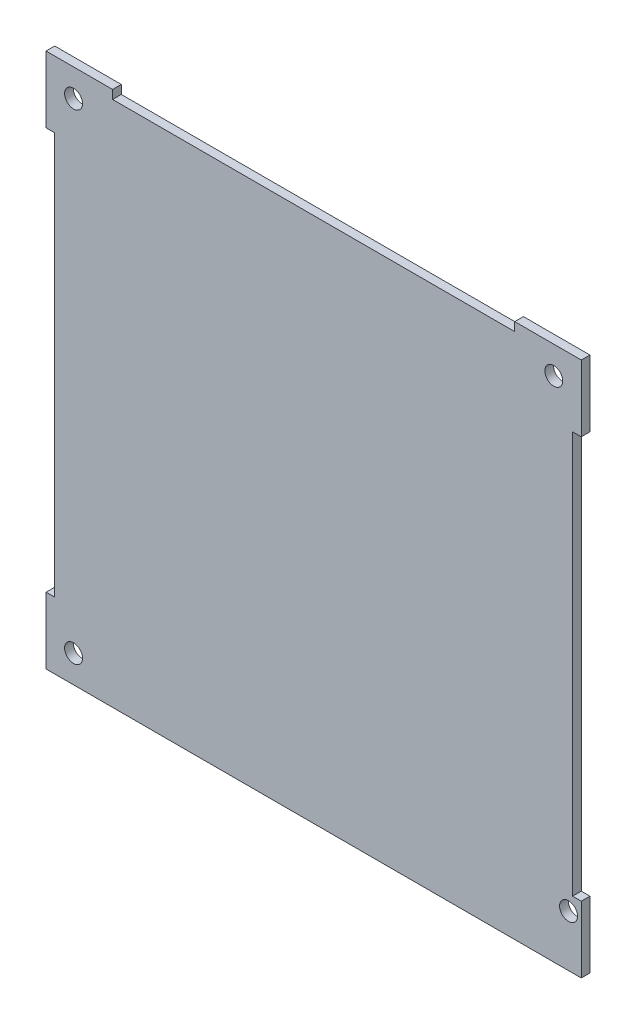
SolidWorks part; units mm, degrees
material "FR4"
ref_plane "Front Plane" through (0, 0, 0) normal (0, 0, 1) x (1, 0, 0)
ref_plane "Top Plane" through (0, 0, 0) normal (0, 1, 0) x (1, 0, 0)
ref_plane "Right Plane" through (0, 0, 0) normal (1, 0, 0) x (0, 0, -1)
sketch "Sketch1" plane through (0, 0, 0) normal (0, 0, 1) x (1, 0, 0)
  line L1 (46.25, -46.25) -> (-46.25, -46.25)
  line L2 (46.25, -46.25) -> (46.25, 46.25)
  line L3 (46.25, 46.25) -> (-46.25, 46.25)
  line L4 (-46.25, -46.25) -> (-46.25, 46.25)
  line L5 (46.25, -46.25) -> (-46.25, 46.25) construction
  line L6 (46.25, 46.25) -> (-46.25, -46.25) construction
  point P0 (0, 0)
  dimension "D1" = 92.5
  dimension "D2" = 92.5
extrude "Boss-Extrude1" add sketch "Sketch1" along normal blind 1.5
hole_wizard "Ø3.1 (3.1) Diameter Hole1" positions "Sketch3" profile "Sketch2" hole size "Ø3.1" standard "ANSI Metric" end condition through all
sketch "Sketch3" plane through (0, 0, 1.5) normal (0, 0, 1) x (1, 0, 0)
  line L0 (46.25, -46.25) -> (46.25, 46.25) construction
  line L1 (-46.25, -46.25) -> (46.25, -46.25) construction
  point P0 (-41.5, 41.5)
  point P2 (41.5, 41.5)
  point P4 (44.05, -37.33)
  point P6 (-41.5, -41.5)
  dimension "D1" = 2.2
  dimension "D2" = 8.92
sketch "Sketch2" plane through (-41.5, 41.5, 1.5) normal (1, 0, 0) x (0, -1, 0)
  line L0 (0, 0) -> (0, 1.5)
  line L1 (0, 1.5) -> (1.55, 1.5)
  line L2 (1.55, 1.5) -> (1.55, 0)
  line L5 (1.55, 0) -> (0, 0)
  line L11 (0, -6.35) -> (0, 107.95) construction
  dimension "Thru Hole Dia." = 3.1
  dimension "Thru Hole Depth" = 1.5
sketch "Sketch4" plane through (0, 0, 0) normal (0, 0, -1) x (-1, 0, 0)
  line L0 (-46.25, -46.25) -> (-46.25, 46.25) construction
  line L1 (-46.25, 34.75) -> (-44.75, 34.75)
  line L2 (-46.25, 34.75) -> (-46.25, -34.75)
  line L3 (-46.25, -34.75) -> (-44.75, -34.75)
  line L4 (-44.75, 34.75) -> (-44.75, -34.75)
  line L5 (-46.25, 46.25) -> (46.25, 46.25) construction
  line L6 (46.25, -46.25) -> (-46.25, -46.25) construction
  line L7 (0, 0) -> (0, 31.1838) construction
  line L8 (44.75, 34.75) -> (44.75, -34.75)
  line L9 (46.25, -34.75) -> (44.75, -34.75)
  line L10 (46.25, 34.75) -> (46.25, -34.75)
  line L11 (46.25, 34.75) -> (44.75, 34.75)
  line L12 (46.25, 46.25) -> (46.25, -46.25) construction
  line L13 (-34.75, 46.25) -> (34.75, 46.25)
  line L14 (-34.75, 46.25) -> (-34.75, 44.75)
  line L15 (-34.75, 44.75) -> (34.75, 44.75)
  line L16 (34.75, 46.25) -> (34.75, 44.75)
  dimension "D1" = 1.5
  dimension "D2" = 11.5
  dimension "D3" = 11.5
  dimension "D4" = 11.5
  dimension "D5" = 11.5
  dimension "D6" = 1.5
extrude "Cut-Extrude1" cut sketch "Sketch4" against normal blind 10
